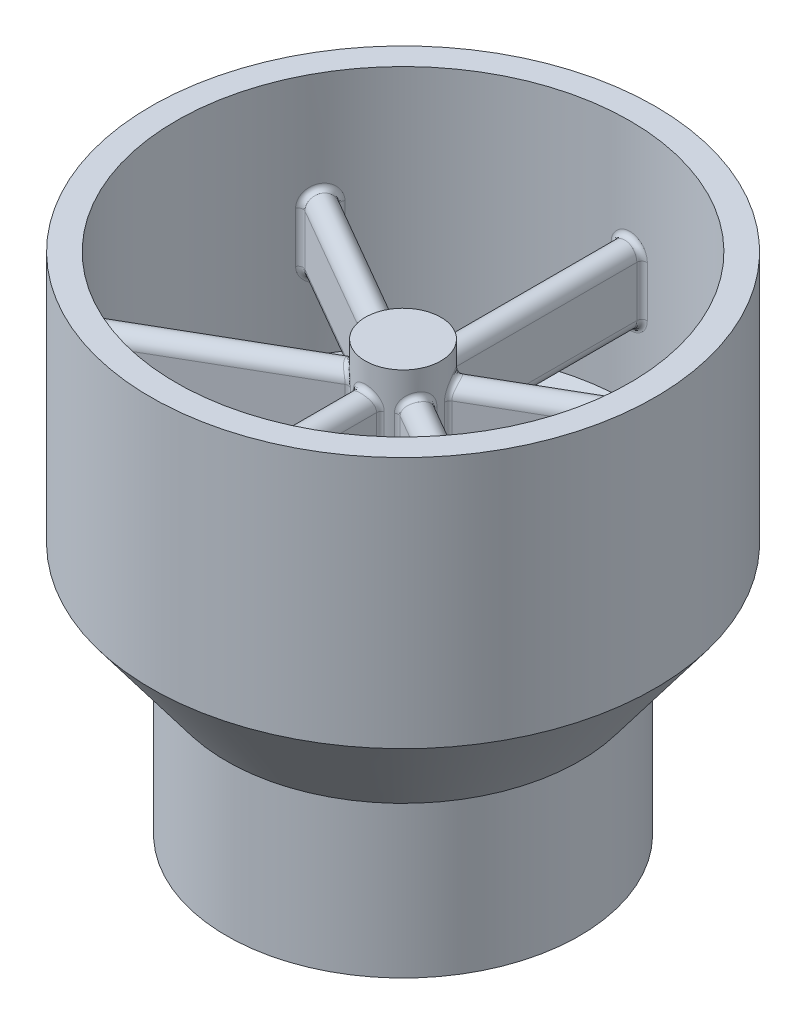
SolidWorks part; units mm, degrees
material "Сталь"
ref_plane "Спереди" through (0, 0, 0) normal (0, 0, 1) x (1, 0, 0)
ref_plane "Сверху" through (0, 0, 0) normal (0, 1, 0) x (1, 0, 0)
ref_plane "Справа" through (0, 0, 0) normal (1, 0, 0) x (0, 0, -1)
sketch "Эскиз1" plane through (0, 0, 0) normal (0, 0, 1) x (1, 0, 0)
  line L0 (0, 0) -> (-50, 0)
  line L1 (-50, 0) -> (-50, -50)
  line L2 (-50, -50) -> (-35, -70)
  line L3 (-35, -70) -> (-35, -100)
  line L4 (-35, -100) -> (0, -100)
  line L5 (0, -100) -> (0, 0)
  line L6 (0, 0) -> (0, 46.546) construction
  dimension "D1" = 50
  dimension "D2" = 100
  dimension "D3" = 50
  dimension "D4" = 35
  dimension "D5" = 30
revolve "Повернуть1" add sketch "Эскиз1" angle 360 about L6
shell "Оболочка3" thickness 5
ref_plane "Плоскость1" through (0, -15, 0) normal (0, 1, 0) x (1, 0, 0)
sketch "Эскиз2" plane through (0, -15, 0) normal (0, 1, 0) x (1, 0, 0)
  circle A0 centre (0, 0) radius 7.5
  dimension "D1" = 15
extrude "Бобышка-Вытянуть1" add sketch "Эскиз2" against normal blind 25 separate body
sketch "Эскиз3" plane through (0, 0, 0) normal (0, 0, 1) x (1, 0, 0)
  line L0 (0, -15) -> (0, -40) construction
  line L1 (7.5, -15) -> (-7.5, -15) construction
  line L2 (-7.5, -40) -> (7.5, -40) construction
  line L3 (0, -32.5) -> (0, -22.5) construction
  line L4 (-2.5, -32.5) -> (-2.5, -22.5)
  line L5 (2.5, -32.5) -> (2.5, -22.5)
  arc A0 (-2.5, -32.5) -> (2.5, -32.5) centre (0, -32.5) ccw
  arc A1 (2.5, -22.5) -> (-2.5, -22.5) centre (0, -22.5) ccw
  point P8 (0, -27.5)
  dimension "D1" = 10
  dimension "D2" = 5
extrude "Бобышка-Вытянуть2" add sketch "Эскиз3" against normal up to surface (44.9305 mm away)
fillet "Скругление1" radius 1 8 edges at (-2.5, -27.5, -44.9305) (-0.2876, -34.9834, -44.9991) (2.5, -27.5, -44.9305) (2.5, -27.5, -7.0711) (0.6049, -30.0743, -7.4756) (-2.5, -27.5, -7.0711) (0.2876, -20.0166, -44.9991) (0.6049, -20.0743, -7.4756)
pattern_circular "Круговой массив1" count 6 over 360 about axis through (0, 0, 0) along (0, -1, 0) of "Бобышка-Вытянуть2", "Скругление1"
